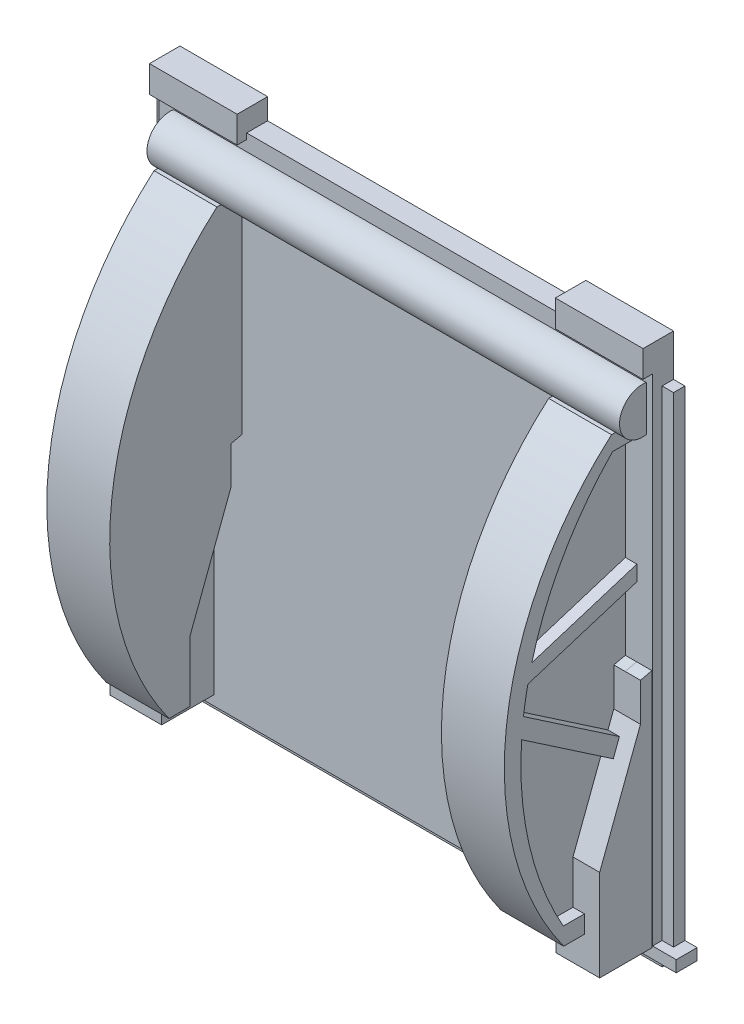
SolidWorks part; units mm, degrees
ref_plane "Front Plane" through (0, 0, 0) normal (0, 0, 1) x (1, 0, 0)
ref_plane "Top Plane" through (0, 0, 0) normal (0, 1, 0) x (1, 0, 0)
ref_plane "Right Plane" through (0, 0, 0) normal (1, 0, 0) x (0, 0, -1)
sketch "Sketch1" plane through (0, 0, 0) normal (0, 0, 1) x (1, 0, 0)
  line L0 (46.0976, 79.2818) -> (69.0976, 79.2818)
  line L1 (69.0976, 79.2818) -> (69.0976, 68.2818)
  line L2 (69.0976, 68.2818) -> (72.0976, 68.2818)
  line L3 (72.0976, 68.2818) -> (72.0976, -57.7182)
  line L4 (72.0976, -57.7182) -> (75.2976, -57.7182)
  line L5 (75.2976, -57.7182) -> (75.2976, -60.7182)
  line L6 (75.2976, -60.7182) -> (69.0976, -60.7182)
  line L7 (69.0976, -60.7182) -> (69.0976, -63.7182)
  line L8 (69.0976, -63.7182) -> (-60.4024, -63.7182)
  line L9 (-60.4024, -63.7182) -> (-60.4024, -60.7182)
  line L10 (-60.4024, -60.7182) -> (-66.6024, -60.7182)
  line L11 (-66.6024, -60.7182) -> (-66.6024, -57.7182)
  line L12 (-66.6024, -57.7182) -> (-63.4024, -57.7182)
  line L13 (-63.4024, -57.7182) -> (-63.4024, 68.2818)
  line L14 (-63.4024, 68.2818) -> (-60.4024, 68.2818)
  line L15 (-60.4024, 68.2818) -> (-60.4024, 79.2818)
  line L16 (-60.4024, 79.2818) -> (-37.4024, 79.2818)
  line L17 (-37.4024, 79.2818) -> (-37.4024, 73.7818)
  line L18 (-37.4024, 73.7818) -> (46.0976, 73.7818)
  line L19 (46.0976, 73.7818) -> (46.0976, 79.2818)
extrude "Boss-Extrude1" add sketch "Sketch1" along normal blind 3
sketch "Sketch2" plane through (0, 0, 3) normal (0, 0, 1) x (1, 0, 0)
  line L0 (75.2976, -57.7182) -> (75.2976, -60.7182)
  line L1 (75.2976, -60.7182) -> (-66.6024, -60.7182)
  line L2 (-66.6024, -60.7182) -> (-66.6024, -57.7182)
  line L3 (-66.6024, -57.7182) -> (-63.4024, -57.7182)
  line L4 (-63.4024, -57.7182) -> (-60.4024, -57.7182)
  line L5 (-60.4024, -57.7182) -> (-60.4024, 79.2818)
  line L6 (75.2976, -57.7182) -> (72.0976, -57.7182)
  line L7 (69.0976, 79.2818) -> (69.0976, -57.7182)
  line L8 (69.0976, -57.7182) -> (72.0976, -57.7182)
  line L9 (69.0976, 79.2818) -> (46.0976, 79.2818)
  line L10 (46.0976, 79.2818) -> (46.0976, 73.7818)
  line L11 (46.0976, 73.7818) -> (-37.4024, 73.7818)
  line L12 (-37.4024, 73.7818) -> (-37.4024, 79.2818)
  line L13 (-60.4024, 79.2818) -> (-37.4024, 79.2818)
extrude "Boss-Extrude2" add sketch "Sketch2" along normal blind 2.5
sketch "Sketch3" plane through (0, 0, 5.5) normal (0, 0, 1) x (1, 0, 0)
  line L4 (69.0976, 79.2818) -> (46.0976, 79.2818)
  line L5 (-60.4024, 79.2818) -> (-37.4024, 79.2818)
  line L10 (69.0976, 79.2818) -> (69.0976, 72.2818)
  line L11 (69.0976, -57.7182) -> (69.0976, 79.2818) construction
  line L12 (46.0976, 79.2818) -> (46.0976, 72.2818)
  line L13 (46.0976, 72.2818) -> (69.0976, 72.2818)
  line L14 (-60.4024, 79.2818) -> (-60.4024, 72.2818)
  line L15 (-60.4024, 79.2818) -> (-60.4024, -57.7182) construction
  line L16 (-60.4024, 72.2818) -> (-37.4024, 72.2818)
  line L17 (-37.4024, 72.2818) -> (-37.4024, 79.2818)
extrude "Boss-Extrude3" add sketch "Sketch3" along normal blind 2.5
ref_plane "Plane1" through (65, 0, 0) normal (1, 0, 0) x (0, 0, -1)
sketch "Sketch4" plane through (65, 0, 0) normal (1, 0, 0) x (0, 0, -1)
  line L0 (-5.5598, 69.5569) -> (-5.5598, 57.7247)
  arc A0 (-5.5598, 57.7247) -> (-5.5598, 69.5569) centre (-6.5597, 63.6408) cw
extrude "Boss-Extrude4" add sketch "Sketch4" against normal blind 121.5 and the other way blind 2.5 separate body
sketch "Sketch5" plane through (65, 0, 0) normal (1, 0, 0) x (0, 0, -1)
  line L0 (-24.7258, -50.2046) -> (-19.2258, -50.2046)
  line L2 (-5.5266, 46.7954) -> (-5.5266, 4.7954)
  line L3 (-5.5266, 4.7954) -> (-8.5266, 4.0954)
  line L4 (-8.5266, 4.0954) -> (-8.5266, -5.9046)
  line L5 (-8.5266, -5.9046) -> (-19.2258, -34.2046)
  line L6 (-19.2258, -34.2046) -> (-19.2258, -50.2046)
  line L7 (-12.1677, 59.7513) -> (-5.5598, 59.7513)
  line L8 (-5.5598, 57.7247) -> (-5.5598, 69.5569) construction
  line L9 (-5.5598, 59.7513) -> (-5.5266, 46.7954)
  arc A0 (-12.1677, 59.7513) -> (-24.7258, -50.2046) centre (41.7903, -2.1063) ccw
extrude "Boss-Extrude5" add sketch "Sketch5" against normal blind 16.5 separate body
sketch "Sketch6" plane through (65, 0, 0) normal (1, 0, 0) x (0, 0, -1)
  line L0 (-5.5806, 4.8563) -> (-8.5806, 4.1563)
  line L1 (-8.5806, 4.1563) -> (-8.5806, -5.8437)
  line L2 (-8.5806, -5.8437) -> (-19.2798, -34.1437)
  line L3 (-19.2798, -34.1437) -> (-19.2798, -58.1437)
  line L4 (-19.2798, -58.1437) -> (-5.5806, -58.1437)
  line L5 (-5.5806, -58.1437) -> (-5.5806, 4.8563)
extrude "Boss-Extrude6" add sketch "Sketch6" along normal blind 4 and the other way blind 7.5
sketch "Sketch8" plane through (65, 0, 0) normal (1, 0, 0) x (0, 0, -1)
  line L0 (-19.2798, -45.5674) -> (-24.8259, -45.5674)
  line L1 (-19.2798, -34.1437) -> (-19.2798, -58.1437) construction
  line L2 (-11.9089, 55.7701) -> (-5.5, 55.7701)
  line L3 (-5.5, -57.7182) -> (-5.5, 72.2818) construction
  line L4 (-5.5, 55.7701) -> (-5.5266, 4.7954)
  line L5 (-5.5266, 4.7954) -> (-8.5806, 4.1563)
  line L6 (-8.5806, 4.1563) -> (-8.5806, -5.8437)
  line L7 (-8.5806, -5.8437) -> (-19.2798, -34.1437)
  line L8 (-19.2798, -34.1437) -> (-19.2798, -45.5674)
  arc A0 (-24.8259, -45.5674) -> (-11.9089, 55.7701) centre (49.112, -3.5) cw
extrude "Cut-Extrude1" cut sketch "Sketch8" against normal blind 3
sketch "Sketch10" plane through (62, 0, 0) normal (1, 0, 0) x (0, 0, -1)
  line L0 (-35.2728, 7.2562) -> (-10.1016, -9.8669)
  line L1 (-19.2798, -34.1437) -> (-8.5806, -5.8437) construction
  line L2 (-10.1016, -9.8669) -> (-11.7095, -14.1199)
  line L3 (-11.7095, -14.1199) -> (-35.7615, 2.2418)
  line L4 (-34.1269, 14.0433) -> (-5.5, 23.0141)
  line L5 (-5.5, -57.7182) -> (-5.5, 72.2818) construction
  line L6 (-5.5, 23.0141) -> (-5.5266, 27.0314)
  line L7 (-5.5266, 4.7954) -> (-5.5266, 46.7954) construction
  line L8 (-5.5266, 27.0314) -> (-33.0898, 18.3939)
  arc A0 (-11.9089, 55.7701) -> (-24.8259, -45.5674) centre (49.112, -3.5) ccw construction
  arc A1 (-35.7615, 2.2418) -> (-35.2728, 7.2562) centre (49.112, -3.5) cw
  arc A2 (-11.9089, 55.7701) -> (-24.8259, -45.5674) centre (49.112, -3.5) ccw construction
  arc A3 (-34.1269, 14.0433) -> (-33.0898, 18.3939) centre (49.112, -3.5) cw
extrude "Boss-Extrude10" add sketch "Sketch10" along normal blind 3
ref_plane "Plane3" through (-55, 0, 0) normal (1, 0, 0) x (0, 0, -1)
sketch "Sketch12" plane through (-55, 0, 0) normal (1, 0, 0) x (0, 0, -1)
  line L0 (-24.765, -50.1964) -> (-19.265, -50.1964)
  line L1 (-5.5658, 46.8036) -> (-5.5658, 4.8036)
  line L2 (-5.5658, 4.8036) -> (-8.5658, 4.1036)
  line L3 (-8.5658, 4.1036) -> (-8.5658, -5.8964)
  line L4 (-8.5658, -5.8964) -> (-19.265, -34.1964)
  line L5 (-19.265, -34.1964) -> (-19.265, -50.1964)
  line L6 (-12.2069, 59.7595) -> (-5.599, 59.7595)
  line L7 (-5.599, 59.7595) -> (-5.5658, 46.8036)
  arc A0 (-12.2069, 59.7595) -> (-24.765, -50.1964) centre (41.751, -2.0981) ccw
extrude "Boss-Extrude11" add sketch "Sketch12" along normal blind 16.5
sketch "Sketch14" plane through (-55, 0, 0) normal (1, 0, 0) x (0, 0, -1)
  line L0 (-19.2665, -45.6674) -> (-24.8126, -45.6674)
  line L1 (-11.8956, 55.6701) -> (-5.4867, 55.6701)
  line L2 (-5.4867, 55.6701) -> (-5.5133, 4.6955)
  line L3 (-5.5133, 4.6955) -> (-8.5673, 4.0563)
  line L4 (-8.5673, 4.0563) -> (-8.5673, -5.9437)
  line L5 (-8.5673, -5.9437) -> (-19.2665, -34.2437)
  line L6 (-19.2665, -34.2437) -> (-19.2665, -45.6674)
  arc A0 (-24.8126, -45.6674) -> (-11.8956, 55.6701) centre (49.1253, -3.5999) cw
extrude "Cut-Extrude4" cut sketch "Sketch14" along normal blind 3
sketch "Sketch15" plane through (-55, 0, 0) normal (1, 0, 0) x (0, 0, -1)
  line L0 (-35.1337, 7.7135) -> (-9.9626, -9.4096)
  line L1 (-9.9626, -9.4096) -> (-11.5705, -13.6626)
  line L2 (-11.5705, -13.6626) -> (-35.6225, 2.6991)
  line L3 (-33.9879, 14.5005) -> (-5.361, 23.4713)
  line L4 (-5.361, 23.4713) -> (-5.3876, 27.4886)
  line L5 (-5.3876, 27.4886) -> (-32.9508, 18.8512)
  arc A0 (-35.6225, 2.6991) -> (-35.1337, 7.7135) centre (49.251, -3.0427) cw
  arc A1 (-33.9879, 14.5005) -> (-32.9508, 18.8512) centre (49.251, -3.0427) cw
extrude "Boss-Extrude12" add sketch "Sketch15" along normal blind 3
sketch "Sketch19" plane through (-55, 0, 0) normal (1, 0, 0) x (0, 0, -1)
  line L0 (-5.5102, 4.8141) -> (-8.5102, 4.1141)
  line L1 (-8.5102, 4.1141) -> (-8.5102, -5.8859)
  line L2 (-8.5102, -5.8859) -> (-19.2093, -34.1859)
  line L3 (-19.2093, -34.1859) -> (-19.2093, -58.1859)
  line L4 (-19.2093, -58.1859) -> (-5.5102, -58.1859)
  line L5 (-5.5102, -58.1859) -> (-5.5102, 4.8141)
extrude "Boss-Extrude17" add sketch "Sketch19" along normal blind 9 and the other way blind 4.5 separate body
